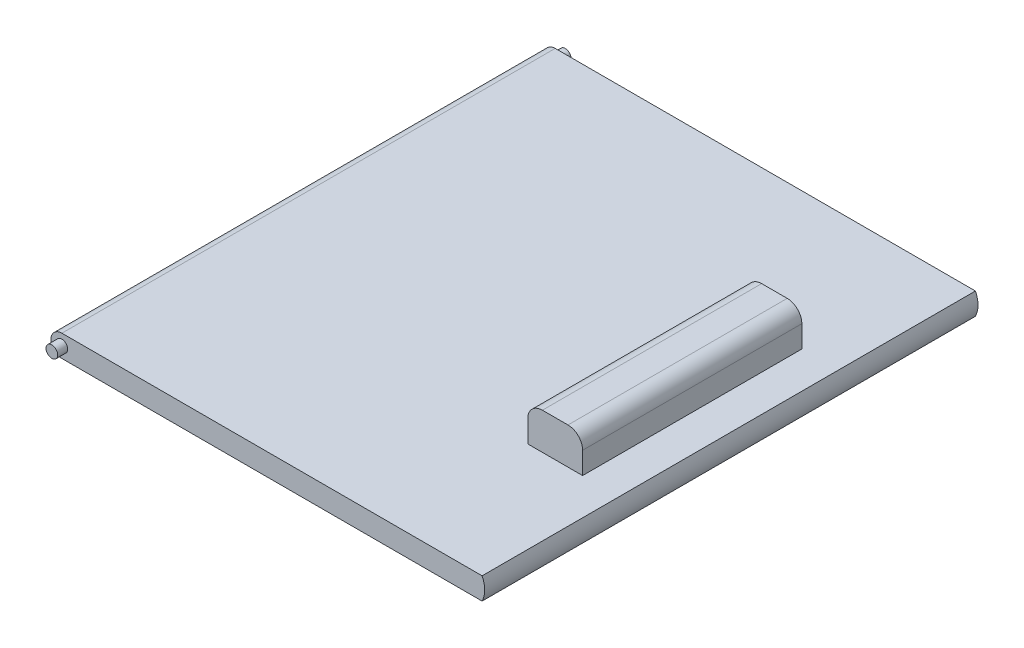
SolidWorks part; units mm, degrees
ref_plane "Front Plane" through (0, 0, 0) normal (0, 0, 1) x (1, 0, 0)
ref_plane "Top Plane" through (0, 0, 0) normal (0, 1, 0) x (1, 0, 0)
ref_plane "Right Plane" through (0, 0, 0) normal (1, 0, 0) x (0, 0, -1)
sketch "Sketch1" plane through (0, 0, 0) normal (0, 0, 1) x (1, 0, 0)
  line L1 (0, -1.5) -> (57.5, -1.5)
  line L3 (0, 1.5) -> (57.5, 1.5)
  line L4 (57.5, -1.5) -> (57.5, 1.5)
  arc A0 (0, 1.5) -> (0, -1.5) centre (0, 0) ccw
  dimension "D2" = 57.5
  dimension "D1" = 3
extrude "Boss-Extrude1" add sketch "Sketch1" along normal blind 67.5
sketch "Sketch2" plane through (0, 0, 67.5) normal (0, 0, 1) x (1, 0, 0)
  circle A0 centre (0, 0) radius 0.8
  dimension "D1" = 1.6
extrude "Boss-Extrude2" add sketch "Sketch2" along normal blind 1.375
sketch "Sketch3" plane through (0, 0, 0) normal (0, 0, -1) x (-1, 0, 0)
  circle A1 centre (0, 0) radius 0.8
  circle A2 centre (0, 0) radius 0.8
  dimension "D1" = 0
extrude "Boss-Extrude3" add sketch "Sketch3" along normal blind 1.375
sketch "Sketch4" plane through (0, 0, 67.5) normal (0, 0, 1) x (1, 0, 0)
  line L0 (57.5, -1.5) -> (57.5, 1.5) construction
  line L1 (57.5, 1.5) -> (0, 1.5) construction
  line L2 (57.5, 1.5) -> (57.5, -1.5)
  arc A0 (57.5, -1.5) -> (57.5, 1.5) centre (54.5, 0) ccw
  point P8 (59, -1.505)
  dimension "D1" = 3
  dimension "D2" = 1.5
extrude "Boss-Extrude4" add sketch "Sketch4" against normal up to surface (67.5 mm away) up to face at (0.8, 0, 0)
sketch "Sketch5" plane through (0, 1.5, 0) normal (0, 1, 0) x (1, 0, 0)
  line L0 (0, -67.5) -> (0, 0) construction
  line L1 (45, -18.75) -> (52.5, -18.75)
  line L2 (45, -18.75) -> (45, -48.75)
  line L3 (45, -48.75) -> (52.5, -48.75)
  line L4 (52.5, -18.75) -> (52.5, -48.75)
  line L5 (57.5, -67.5) -> (57.5, 0) construction
  point P6 (0, -33.75)
  point P7 (45, -33.75)
  dimension "D1" = 30
  dimension "D2" = 7.5
  dimension "D3" = 5
extrude "Boss-Extrude5" add sketch "Sketch5" along normal blind 5
fillet "Fillet1" radius 2 2 edges at (45, 6.5, 33.75) (52.5, 6.5, 33.75)
